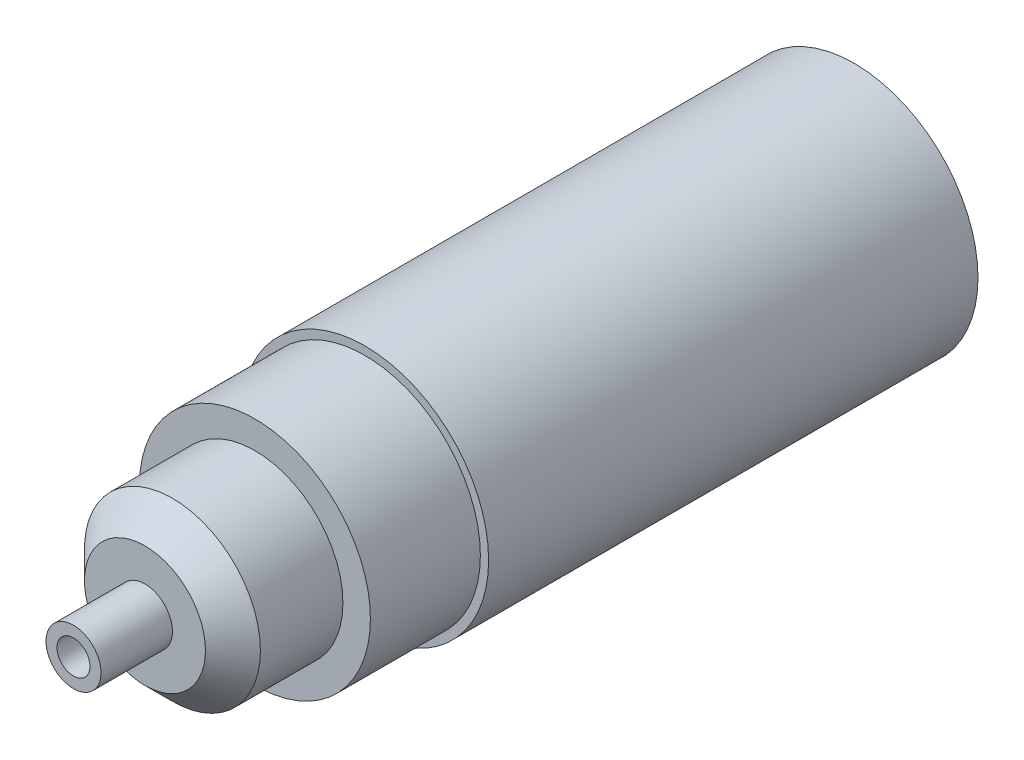
SolidWorks part; units mm, degrees
ref_plane "Front Plane" through (0, 0, 0) normal (0, 0, 1) x (1, 0, 0)
ref_plane "Top Plane" through (0, 0, 0) normal (0, 1, 0) x (1, 0, 0)
ref_plane "Right Plane" through (0, 0, 0) normal (1, 0, 0) x (0, 0, -1)
sketch "Sketch1" plane through (0, 0, 0) normal (0, 0, 1) x (1, 0, 0)
  circle A0 centre (0, 0) radius 22.5
  dimension "D1" = 45
extrude "Boss-Extrude1" add sketch "Sketch1" along normal blind 89
sketch "Sketch2" plane through (0, 0, 89) normal (0, 0, 1) x (1, 0, 0)
  circle A0 centre (0, 0) radius 21
  dimension "D1" = 42
extrude "Boss-Extrude2" add sketch "Sketch2" along normal blind 20
sketch "Sketch3" plane through (0, 0, 109) normal (0, 0, 1) x (1, 0, 0)
  circle A1 centre (0, 0) radius 16
  dimension "D1" = 32
extrude "Boss-Extrude3" add sketch "Sketch3" along normal blind 20
chamfer "Chamfer1" distance 5 angle 45 1 edges at (16, 0, 129)
sketch "Sketch4" plane through (0, 0, 129) normal (0, 0, 1) x (1, 0, 0)
  circle A0 centre (0, 0) radius 5
  dimension "D1" = 10
extrude "Boss-Extrude4" add sketch "Sketch4" along normal blind 13
sketch "Sketch5" plane through (0, 0, 142) normal (0, 0, 1) x (1, 0, 0)
  circle A0 centre (0, 0) radius 3
  dimension "D1" = 6
extrude "Cut-Extrude1" cut sketch "Sketch5" against normal blind 10
